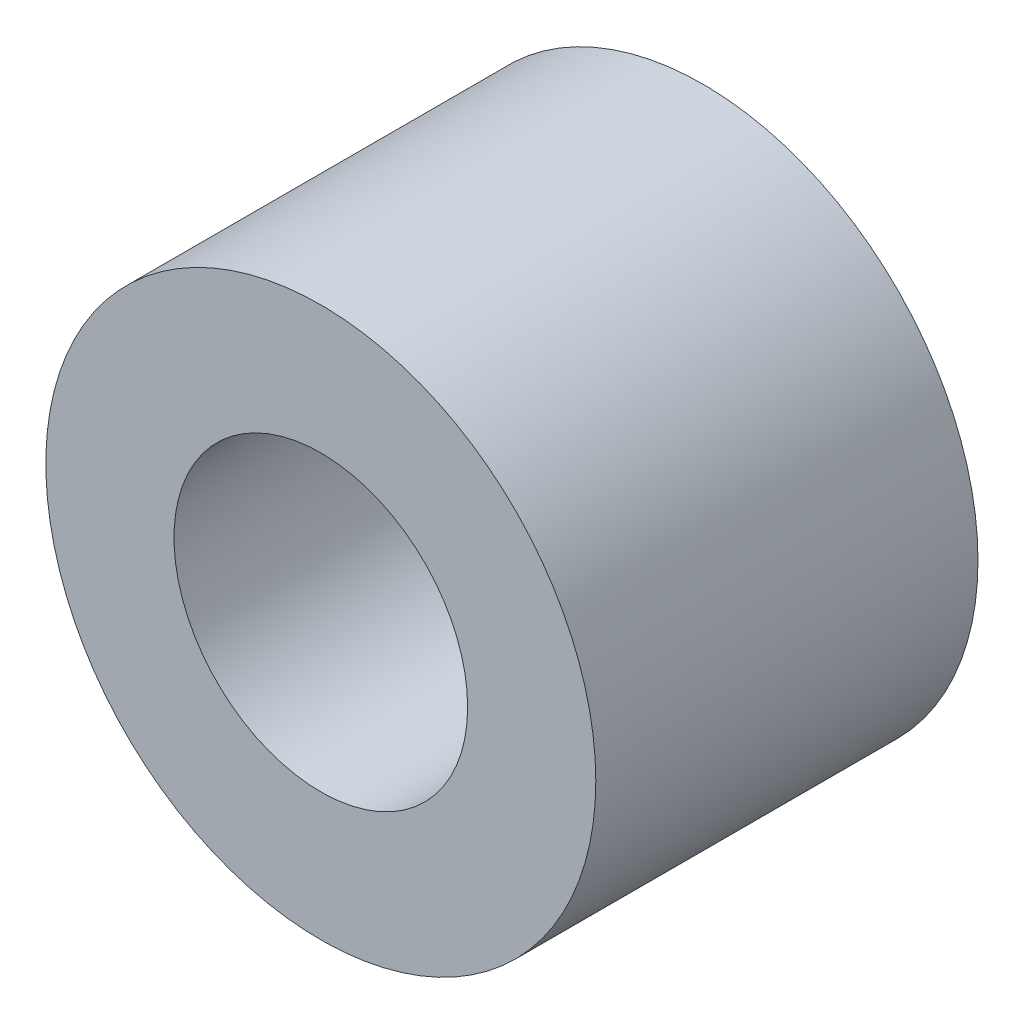
SolidWorks part; units mm, degrees
ref_plane "Plan de face" through (0, 0, 0) normal (0, 0, 1) x (1, 0, 0)
ref_plane "Plan de dessus" through (0, 0, 0) normal (0, 1, 0) x (1, 0, 0)
ref_plane "Plan de droite" through (0, 0, 0) normal (1, 0, 0) x (0, 0, -1)
sketch "Esquisse1" plane through (0, 0, 0) normal (0, 0, 1) x (1, 0, 0)
  circle A0 centre (0, 0) radius 2.95
  circle A1 centre (0, 0) radius 1.575
extrude "Boss.-Extru.1" add sketch "Esquisse1" along normal blind 4.1
